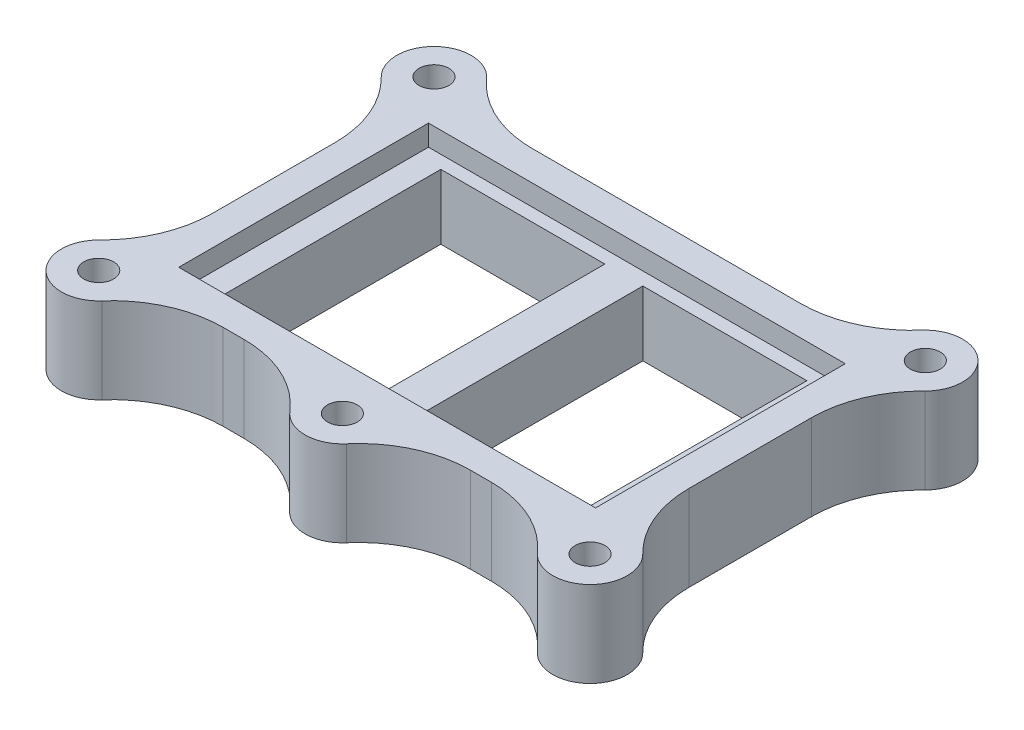
SolidWorks part; units mm, degrees
ref_plane "Front Plane" through (0, 0, 0) normal (0, 0, 1) x (1, 0, 0)
ref_plane "Top Plane" through (0, 0, 0) normal (0, 1, 0) x (1, 0, 0)
ref_plane "Right Plane" through (0, 0, 0) normal (1, 0, 0) x (0, 0, -1)
sketch "Sketch1" plane through (0, 0, 0) normal (0, 1, 0) x (1, 0, 0)
  line L0 (-2.55, 15) -> (2.55, -15) construction
  line L1 (-24.55, 15) -> (-2.55, 15)
  line L2 (-24.55, 15) -> (-24.55, -15)
  line L3 (-24.55, -15) -> (-2.55, -15)
  line L4 (-2.55, 15) -> (-2.55, -15)
  line L5 (2.55, 15) -> (24.55, 15)
  line L6 (2.55, 15) -> (2.55, -15)
  line L7 (2.55, -15) -> (24.55, -15)
  line L8 (24.55, 15) -> (24.55, -15)
  line L9 (-26.45, 16.75) -> (-26.45, -16.75) construction
  line L10 (-24.95, 15.25) -> (24.95, 15.25) construction
  line L11 (-24.95, 15.25) -> (-24.95, -15.25) construction
  line L12 (-24.95, -15.25) -> (24.95, -15.25) construction
  line L13 (24.95, 15.25) -> (24.95, -15.25) construction
  line L14 (-26.45, -16.75) -> (26.45, -16.75)
  line L15 (26.45, 16.75) -> (26.45, -16.75) construction
  line L16 (-26.45, 16.75) -> (26.45, 16.75)
  line L17 (-26.45, 16.75) -> (-27.95, 16.75)
  line L18 (-27.95, 16.75) -> (-27.95, -16.75)
  line L19 (-27.95, -16.75) -> (-26.45, -16.75)
  line L20 (26.45, -16.75) -> (27.95, -16.75)
  line L21 (27.95, -16.75) -> (27.95, 16.75)
  line L22 (27.95, 16.75) -> (26.45, 16.75)
  point P13 (0, 15.25)
  point P14 (24.95, 0)
  dimension "D1" = 22
  dimension "D2" = 30
  dimension "D3" = 5.1
  dimension "D4" = 30.5
  dimension "D5" = 0.4
  dimension "D7" = 1.5
  dimension "D6" = 1.5
extrude "Boss-Extrude1" add sketch "Sketch1" along normal blind 8.7
sketch "Sketch2" plane through (0, 0, 0) normal (0, -1, 0) x (1, 0, 0)
  line L0 (-31.95, 20.75) -> (-31.95, -20.75)
  line L1 (-27.95, 16.75) -> (27.95, 16.75)
  line L2 (-27.95, 16.75) -> (-27.95, -16.75)
  line L3 (-27.95, -16.75) -> (27.95, -16.75)
  line L4 (27.95, 16.75) -> (27.95, -16.75)
  line L5 (-31.95, -20.75) -> (31.95, -20.75)
  line L6 (31.95, 20.75) -> (31.95, -20.75)
  line L7 (-31.95, 20.75) -> (31.95, 20.75)
  dimension "D1" = 4
extrude "Boss-Extrude2" add sketch "Sketch2" against normal blind 11.5
sketch "Sketch3" plane through (0, 11.5, 0) normal (0, 1, 0) x (1, 0, 0)
  line L0 (31.95, -20.75) -> (-31.95, -20.75) construction
  line L1 (-31.95, -20.75) -> (-31.95, 20.75) construction
  circle A0 centre (-32.95, 22.4821) radius 2
  circle A1 centre (-32.95, 22.4821) radius 5
  circle A2 centre (-32.95, -22.4821) radius 2
  circle A3 centre (-32.95, -22.4821) radius 5
  circle A4 centre (32.95, -22.4821) radius 2
  circle A5 centre (32.95, -22.4821) radius 5
  circle A6 centre (32.95, 22.4821) radius 2
  circle A7 centre (32.95, 22.4821) radius 5
  circle A8 centre (0, -22.75) radius 5
  circle A9 centre (0, -22.75) radius 2
  dimension "D1" = 4
  dimension "D2" = 10
  dimension "D3" = 1
extrude "Boss-Extrude3" add sketch "Sketch3" against normal blind 8.5
sketch "Sketch4" plane through (0, 3, 0) normal (0, -1, 0) x (1, 0, 0)
  circle A0 centre (-32.95, -22.4821) radius 5
  circle A1 centre (-32.95, 22.4821) radius 5
  circle A2 centre (0, 22.75) radius 5
  circle A3 centre (32.95, 22.4821) radius 5
  circle A4 centre (32.95, -22.4821) radius 5
extrude "Boss-Extrude4" add sketch "Sketch4" along normal blind 3
fillet "Fillet2" radius 15 10 edges at (-28.2596, 5.75, 20.75) (-31.95, 5.75, 17.5831) (-31.95, 5.75, -17.5831) (-28.2596, 5.75, -20.75) (28.2596, 5.75, -20.75) (31.95, 5.75, -17.5831) (31.95, 5.75, 17.5831) (28.2596, 5.75, 20.75) (-4.5826, 5.75, 20.75) (4.5826, 5.75, 20.75)
